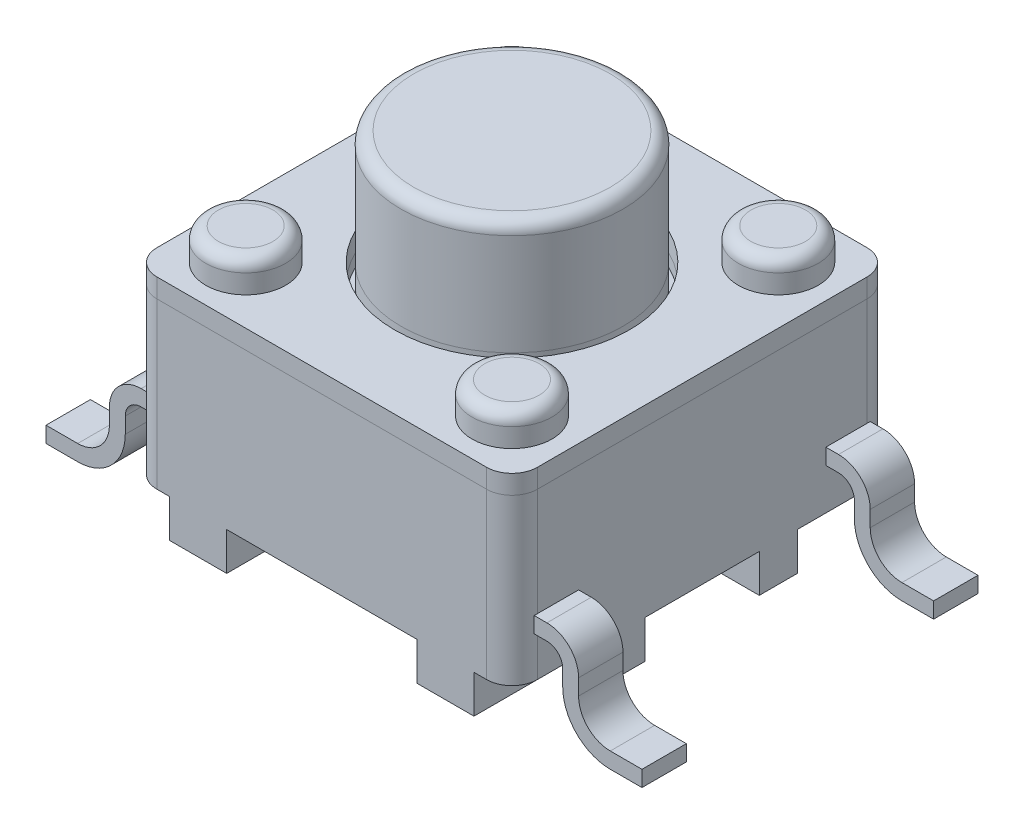
SolidWorks part; units mm, degrees
ref_plane "Спереди" through (0, 0, 0) normal (0, 0, 1) x (1, 0, 0)
ref_plane "Сверху" through (0, 0, 0) normal (0, 1, 0) x (1, 0, 0)
ref_plane "Справа" through (0, 0, 0) normal (1, 0, 0) x (0, 0, -1)
other "Configuration Table"
sketch "Эскиз1" plane through (0, 0, 0) normal (0, 1, 0) x (1, 0, 0)
  line L0 (-3, 0) -> (3, 0) construction
  line L1 (-3, 3) -> (3, 3) construction
  line L2 (-3, 3) -> (-3, -3) construction
  line L3 (-3, -3) -> (3, -3) construction
  line L4 (3, 3) -> (3, -3) construction
  line L5 (-3, 3) -> (3, -3) construction
  line L6 (-3, -3) -> (3, 3) construction
  line L7 (3, 0.9) -> (-3, 0.9)
  line L8 (3, 0.9) -> (3, 1.5)
  line L9 (3, 1.5) -> (2.4, 1.5)
  line L10 (2.4, 1.5) -> (2.4, 3)
  line L11 (2.4, 3) -> (1.5, 3)
  line L12 (1.5, 3) -> (1.5, 1.5)
  line L13 (1.5, 1.5) -> (-1.5, 1.5)
  line L14 (0, 3) -> (0, -3) construction
  line L15 (-3, 0.9) -> (-3, 1.5)
  line L16 (-3, 1.5) -> (-2.4, 1.5)
  line L17 (-2.4, 1.5) -> (-2.4, 3)
  line L18 (-2.4, 3) -> (-1.5, 3)
  line L19 (-1.5, 3) -> (-1.5, 1.5)
  line L20 (1.5, -3) -> (1.5, -1.5)
  line L21 (2.4, -3) -> (1.5, -3)
  line L22 (2.4, -1.5) -> (2.4, -3)
  line L23 (3, -1.5) -> (2.4, -1.5)
  line L24 (3, -0.9) -> (3, -1.5)
  line L25 (3, -0.9) -> (-3, -0.9)
  line L26 (-3, -0.9) -> (-3, -1.5)
  line L27 (-3, -1.5) -> (-2.4, -1.5)
  line L28 (-2.4, -1.5) -> (-2.4, -3)
  line L29 (-2.4, -3) -> (-1.5, -3)
  line L30 (-1.5, -3) -> (-1.5, -1.5)
  line L31 (1.5, -1.5) -> (-1.5, -1.5)
  point P0 (0, 0)
  point P21 (0, 1.5)
  point P22 (0, 0.9)
  dimension "D1" = 6
  dimension "D2" = 6
  dimension "D3" = 3
  dimension "D4" = 0.9
  dimension "D5" = 0.6
  dimension "D6" = 1.8
extrude "Бобышка-Вытянуть1" add sketch "Эскиз1" along normal blind 0.6
sketch "Эскиз2" plane through (0, 0.6, 0) normal (0, 1, 0) x (1, 0, 0)
  line L1 (-3, 3) -> (3, 3)
  line L2 (-3, 3) -> (-3, -3)
  line L3 (-3, -3) -> (3, -3)
  line L4 (3, 3) -> (3, -3)
  line L5 (-3, 3) -> (3, -3) construction
  line L6 (-3, -3) -> (3, 3) construction
  point P0 (0, 0)
  dimension "D1" = 6
  dimension "D2" = 6
extrude "Бобышка-Вытянуть2" add sketch "Эскиз2" along normal blind 2.9
sketch "Эскиз4" plane through (0, 0, 3) normal (0, 0, 1) x (1, 0, 0)
  line L0 (3, 1.5) -> (3.2, 1.5)
  line L1 (3, 3.5) -> (3, 0.6) construction
  line L2 (3.7, 1) -> (3.7, 0.75)
  line L3 (4.2, 0.25) -> (4.7, 0.25)
  line L5 (1.5, 0.6) -> (1.5, 0) construction
  line L6 (-3, 3.5) -> (3, 3.5) construction
  line L7 (1.5, 0) -> (2.4, 0) construction
  arc A0 (3.7, 0.75) -> (4.2, 0.25) centre (4.2, 0.75) ccw
  arc A1 (3.2, 1.5) -> (3.7, 1) centre (3.2, 1) cw
  point P14 (3.7, 0.25)
  point P17 (3.7, 1.5)
  dimension "D6" = 0.5
  dimension "D1" = 0.7
  dimension "D2" = 1
  dimension "D3" = 3.2
  dimension "D4" = 2
  dimension "D5" = 0.25
extrude "Вытянуть-Тонкостенный1" add sketch "Эскиз4" against normal blind 0.7 from offset 0.35 separate body thin offset against normal yes
mirror "Зеркальное отражение1" about plane through (0, 0, 0) normal (0, 0, 1) of bodies 106
mirror "Зеркальное отражение2" about plane through (0, 0, 0) normal (1, 0, 0) of bodies 106 107
sketch "Эскиз5" plane through (0, 3.5, 0) normal (0, 1, 0) x (1, 0, 0)
  circle A0 centre (0, 0) radius 1.75
  dimension "D1" = 3.5
extrude "Бобышка-Вытянуть3" add sketch "Эскиз5" along normal blind 1.8 separate body
sketch "Эскиз6" plane through (0, 3.5, 0) normal (0, 1, 0) x (1, 0, 0)
  line L1 (-2.1, 2.1) -> (2.1, 2.1) construction
  line L2 (-2.1, 2.1) -> (-2.1, -2.1) construction
  line L3 (-2.1, -2.1) -> (2.1, -2.1) construction
  line L4 (2.1, 2.1) -> (2.1, -2.1) construction
  line L5 (-2.1, 2.1) -> (2.1, -2.1) construction
  line L6 (-2.1, -2.1) -> (2.1, 2.1) construction
  circle A0 centre (-2.1, 2.1) radius 0.63
  circle A1 centre (2.1, 2.1) radius 0.63
  circle A2 centre (2.1, -2.1) radius 0.63
  circle A3 centre (-2.1, -2.1) radius 0.63
  point P0 (0, 0)
  dimension "D3" = 1.26
  dimension "D1" = 4.2
  dimension "D2" = 4.2
extrude "Бобышка-Вытянуть4" add sketch "Эскиз6" along normal blind 0.5 separate body
fillet "Скругление1" radius 0.2 1 edges at (2.1, 4, 2.73)
fillet "Скругление2" radius 0.2 1 edges at (-2.1, 4, 2.73)
fillet "Скругление3" radius 0.2 1 edges at (-2.1, 4, -1.47)
fillet "Скругление4" radius 0.2 1 edges at (2.1, 4, -1.47)
fillet "Скругление5" radius 0.2 1 edges at (0, 5.3, 1.75)
fillet "Скругление6" radius 0.4 4 edges at (-3, 2.05, -3) (3, 2.05, -3) (-3, 2.05, 3) (3, 2.05, 3)
sketch "Эскиз7" plane through (0, 3.5, 0) normal (0, 1, 0) x (1, 0, 0)
  circle A1 centre (0, 0) radius 1.75 construction
  circle A2 centre (0, 0) radius 1.85
  circle A3 centre (0, 0) radius 1.85
  circle A4 centre (0, 0) radius 1.75
  dimension "D1" = 0.1
extrude "Вырез-Вытянуть1" cut sketch "Эскиз7" against normal blind 0.5
ref_plane "Плоскость1" through (0, 3.2, 0) normal (0, 1, 0) x (1, 0, 0)
sketch "Эскиз8" plane through (0, 3.2, 0) normal (0, 1, 0) x (1, 0, 0)
  line L1 (-4.5281, 3.796) -> (4.5281, 3.796)
  line L2 (-4.5281, 3.796) -> (-4.5281, -3.796)
  line L3 (-4.5281, -3.796) -> (4.5281, -3.796)
  line L4 (4.5281, 3.796) -> (4.5281, -3.796)
  line L5 (-4.5281, 3.796) -> (4.5281, -3.796) construction
  line L6 (-4.5281, -3.796) -> (4.5281, 3.796) construction
  point P0 (0, 0)
surface "Поверхность-Плоскость1" sketch "Эскиз8"
split "Разделить1" trimming surface bodies 116 bodies to split 115 resulting bodies 117 118 119
